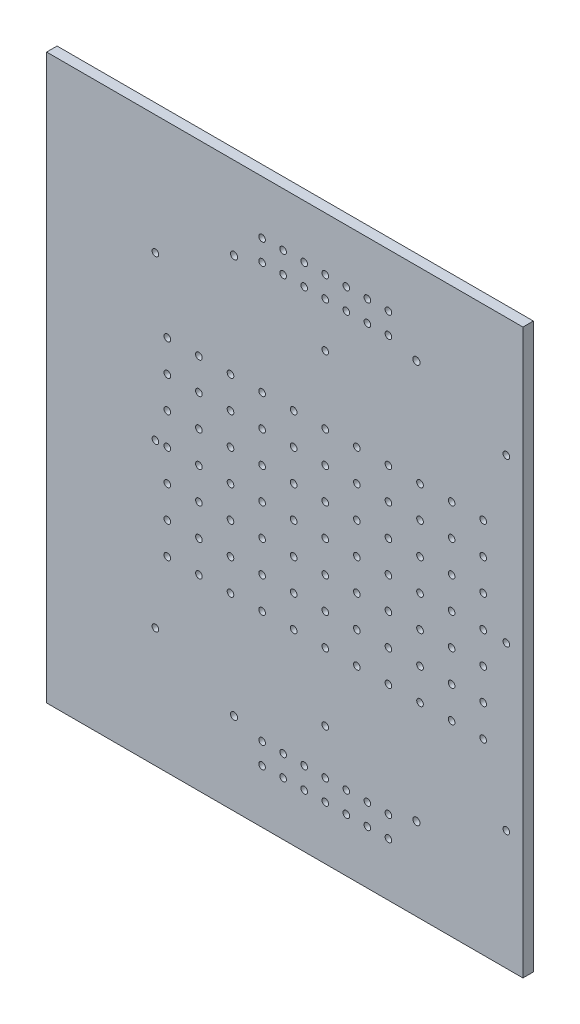
SolidWorks part; units mm, degrees
ref_plane "Front Plane" through (0, 0, 0) normal (0, 0, 1) x (1, 0, 0)
ref_plane "Top Plane" through (0, 0, 0) normal (0, 1, 0) x (1, 0, 0)
ref_plane "Right Plane" through (0, 0, 0) normal (1, 0, 0) x (0, 0, -1)
sketch "Sketch1" plane through (0, 0, 0) normal (0, 0, 1) x (1, 0, 0)
  line L1 (-143.635, 170) -> (143.635, 170)
  line L2 (-143.635, 170) -> (-143.635, -170)
  line L3 (-143.635, -170) -> (143.635, -170)
  line L4 (143.635, 170) -> (143.635, -170)
  dimension "D1" = 287.27
  dimension "D2" = 340
  dimension "D3" = 170
  dimension "D4" = 143.635
extrude "Base_Plate-Extrude" add sketch "Sketch1" along normal blind 6.3
sketch "Sketch3" plane through (0, 0, 6.3) normal (0, 0, 1) x (1, 0, 0)
  line L0 (218.6774, 98) -> (-212.5391, 98) construction
  line L1 (218.7113, -98) -> (-212.5283, -98) construction
  line L2 (133.635, 226.7998) -> (133.635, -231.3038) construction
  line L3 (143.635, -170) -> (143.635, 170) construction
  line L4 (-78.025, 174.4237) -> (-78.025, -178.7911) construction
  line L5 (412.3614, 0) -> (1049.4297, 0) construction
  line L6 (79.415, 225.6084) -> (79.415, -232.4952) construction
  line L7 (-30.585, -232.4952) -> (-30.585, 225.6084) construction
  line L8 (95.7553, 120.25) -> (-187.2723, 120.25) construction
  line L9 (88.1602, -120.25) -> (-163.8184, -120.25) construction
  circle A0 centre (133.635, 98) radius 2
  circle A1 centre (24.415, 98) radius 2
  circle A2 centre (-78.025, 98) radius 2
  circle A3 centre (-78.025, -98) radius 2
  circle A4 centre (24.415, -98) radius 2
  circle A5 centre (133.635, -98) radius 2
  circle A8 centre (133.635, 0) radius 2
  circle A9 centre (-78.025, 0) radius 2
  circle A85 centre (79.415, -120.25) radius 2.15
  circle A86 centre (-30.585, -120.25) radius 2.15
  circle A87 centre (-30.585, 120.25) radius 2.15
  circle A88 centre (79.415, 120.25) radius 2.15
  dimension "D1" = 4
  dimension "D8" = 4
  dimension "D9" = 4
  dimension "D10" = 4
  dimension "D11" = 4
  dimension "D12" = 4
  dimension "D16" = 4
  dimension "D17" = 4
  dimension "D20" = 4.3
  dimension "D21" = 4.3
  dimension "D22" = 4.3
  dimension "D23" = 4.3
  dimension "D3" = 109.22
  dimension "D4" = 102.44
  dimension "D5" = 102.44
  dimension "D6" = 109.22
  dimension "D2" = 196
  dimension "D7" = 98
  dimension "D13" = 10
  dimension "D14" = 98
  dimension "D15" = 98
  dimension "D18" = 110
  dimension "D19" = 240.5
  dimension "D24" = 120.25
  dimension "D25" = 55
extrude "Plate_to_Plate_Mnt-Thru-Hole" cut sketch "Sketch3" against normal through all
sketch "Sketch4" plane through (0, 0, 6.3) normal (0, 0, 1) x (1, 0, 0)
  line L0 (283.705, 0) -> (-313.8392, 0) construction
  circle A0 centre (-70.835, 0) radius 2
  circle A1 centre (-78.025, 0) radius 2 construction
  circle A2 centre (-51.785, 0) radius 2
  circle A3 centre (-32.735, 0) radius 2
  circle A4 centre (-13.685, 0) radius 2
  circle A5 centre (5.365, 0) radius 2
  circle A6 centre (24.415, 0) radius 2
  circle A7 centre (43.465, 0) radius 2
  circle A8 centre (62.515, 0) radius 2
  circle A9 centre (81.565, 0) radius 2
  circle A10 centre (100.615, 0) radius 2
  circle A11 centre (119.665, 0) radius 2
  circle A12 centre (-70.835, 19.05) radius 2
  circle A13 centre (-51.785, 19.05) radius 2
  circle A14 centre (-32.735, 19.05) radius 2
  circle A15 centre (-13.685, 19.05) radius 2
  circle A16 centre (5.365, 19.05) radius 2
  circle A17 centre (24.415, 19.05) radius 2
  circle A18 centre (43.465, 19.05) radius 2
  circle A19 centre (62.515, 19.05) radius 2
  circle A20 centre (81.565, 19.05) radius 2
  circle A21 centre (100.615, 19.05) radius 2
  circle A22 centre (119.665, 19.05) radius 2
  circle A23 centre (-70.835, 38.1) radius 2
  circle A24 centre (-51.785, 38.1) radius 2
  circle A25 centre (-32.735, 38.1) radius 2
  circle A26 centre (-13.685, 38.1) radius 2
  circle A27 centre (5.365, 38.1) radius 2
  circle A28 centre (24.415, 38.1) radius 2
  circle A29 centre (43.465, 38.1) radius 2
  circle A30 centre (62.515, 38.1) radius 2
  circle A31 centre (81.565, 38.1) radius 2
  circle A32 centre (100.615, 38.1) radius 2
  circle A33 centre (119.665, 38.1) radius 2
  circle A34 centre (-70.835, 57.15) radius 2
  circle A35 centre (-51.785, 57.15) radius 2
  circle A36 centre (-32.735, 57.15) radius 2
  circle A37 centre (-13.685, 57.15) radius 2
  circle A38 centre (5.365, 57.15) radius 2
  circle A39 centre (24.415, 57.15) radius 2
  circle A40 centre (43.465, 57.15) radius 2
  circle A41 centre (62.515, 57.15) radius 2
  circle A42 centre (81.565, 57.15) radius 2
  circle A43 centre (100.615, 57.15) radius 2
  circle A44 centre (119.665, 57.15) radius 2
  circle A45 centre (-70.835, -19.05) radius 2
  circle A46 centre (-51.785, -19.05) radius 2
  circle A47 centre (-32.735, -19.05) radius 2
  circle A48 centre (-13.685, -19.05) radius 2
  circle A49 centre (5.365, -19.05) radius 2
  circle A50 centre (24.415, -19.05) radius 2
  circle A51 centre (43.465, -19.05) radius 2
  circle A52 centre (62.515, -19.05) radius 2
  circle A53 centre (81.565, -19.05) radius 2
  circle A54 centre (100.615, -19.05) radius 2
  circle A55 centre (119.665, -19.05) radius 2
  circle A56 centre (-70.835, -38.1) radius 2
  circle A57 centre (-51.785, -38.1) radius 2
  circle A58 centre (-32.735, -38.1) radius 2
  circle A59 centre (-13.685, -38.1) radius 2
  circle A60 centre (5.365, -38.1) radius 2
  circle A61 centre (24.415, -38.1) radius 2
  circle A62 centre (43.465, -38.1) radius 2
  circle A63 centre (62.515, -38.1) radius 2
  circle A64 centre (81.565, -38.1) radius 2
  circle A65 centre (100.615, -38.1) radius 2
  circle A66 centre (119.665, -38.1) radius 2
  circle A67 centre (-70.835, -57.15) radius 2
  circle A68 centre (-51.785, -57.15) radius 2
  circle A69 centre (-32.735, -57.15) radius 2
  circle A70 centre (-13.685, -57.15) radius 2
  circle A71 centre (5.365, -57.15) radius 2
  circle A72 centre (24.415, -57.15) radius 2
  circle A73 centre (43.465, -57.15) radius 2
  circle A74 centre (62.515, -57.15) radius 2
  circle A75 centre (81.565, -57.15) radius 2
  circle A76 centre (100.615, -57.15) radius 2
  circle A77 centre (119.665, -57.15) radius 2
  dimension "D1" = 7.19
  dimension "D2" = 4
  dimension "D4" = 11
  dimension "D3" = 4
  dimension "D5" = 4
extrude "Center_Perforation-Thru-Hole" cut sketch "Sketch4" against normal through all
sketch "Sketch5" plane through (0, 0, 6.3) normal (0, 0, 1) x (1, 0, 0)
  line L0 (300.3422, 0) -> (-331.6581, 0) construction
  line L1 (24.415, -98) -> (24.415, 98) construction
  circle A0 centre (24.415, -125.08) radius 2
  circle A1 centre (24.415, -98) radius 2 construction
  circle A2 centre (37.115, -125.08) radius 2
  circle A3 centre (49.815, -125.08) radius 2
  circle A4 centre (62.515, -125.08) radius 2
  circle A5 centre (11.715, -125.08) radius 2
  circle A6 centre (-0.985, -125.08) radius 2
  circle A7 centre (-13.685, -125.08) radius 2
  circle A8 centre (24.415, -137.78) radius 2
  circle A9 centre (37.115, -137.78) radius 2
  circle A10 centre (49.815, -137.78) radius 2
  circle A11 centre (62.515, -137.78) radius 2
  circle A12 centre (11.715, -137.78) radius 2
  circle A13 centre (-0.985, -137.78) radius 2
  circle A14 centre (-13.685, -137.78) radius 2
  circle A15 centre (-13.685, 137.78) radius 2
  circle A16 centre (-0.985, 137.78) radius 2
  circle A17 centre (11.715, 137.78) radius 2
  circle A18 centre (62.515, 137.78) radius 2
  circle A19 centre (49.815, 137.78) radius 2
  circle A20 centre (37.115, 137.78) radius 2
  circle A21 centre (24.415, 137.78) radius 2
  circle A22 centre (-13.685, 125.08) radius 2
  circle A23 centre (-0.985, 125.08) radius 2
  circle A24 centre (11.715, 125.08) radius 2
  circle A25 centre (62.515, 125.08) radius 2
  circle A26 centre (49.815, 125.08) radius 2
  circle A27 centre (37.115, 125.08) radius 2
  circle A28 centre (24.415, 125.08) radius 2
  dimension "D1" = 27.08
  dimension "D2" = 4
  dimension "D3" = 4
  dimension "D5" = 4
  dimension "D4" = 2
extrude "Side-Perforation-Thru-Hole" cut sketch "Sketch5" against normal through all
equation "\"D3@Sketch1\"=\"D2@Sketch1\"/2"
equation "\"D4@Sketch1\"=\"D1@Sketch1\"/2"
equation "\"PLATE_LEN\"= 287.27"
equation "\"D1@Sketch1\"=\"PLATE_LEN\""
equation "\"PLATE_WID\"= 340"
equation "\"D2@Sketch1\"=\"PLATE_WID\""
equation "\"PLATE_THICKNESS\"=6.3"
equation "\"D1@Base_Plate-Extrude\" = \"PLATE_THICKNESS\""
equation "\"FRONT_TO_TRIPOD\"=110"
equation "\"TRIPOD_STRIDE\"=340"
equation "\"D7@Sketch3\"=\"D2@Sketch3\"/2"
equation "\"D14@Sketch3\"=\"D2@Sketch3\"/2"
equation "\"D15@Sketch3\"=\"D2@Sketch3\"/2"
equation "\"D24@Sketch3\"=\"D19@Sketch3\"/2"
equation "\"D25@Sketch3\"=\"D18@Sketch3\"/2"
